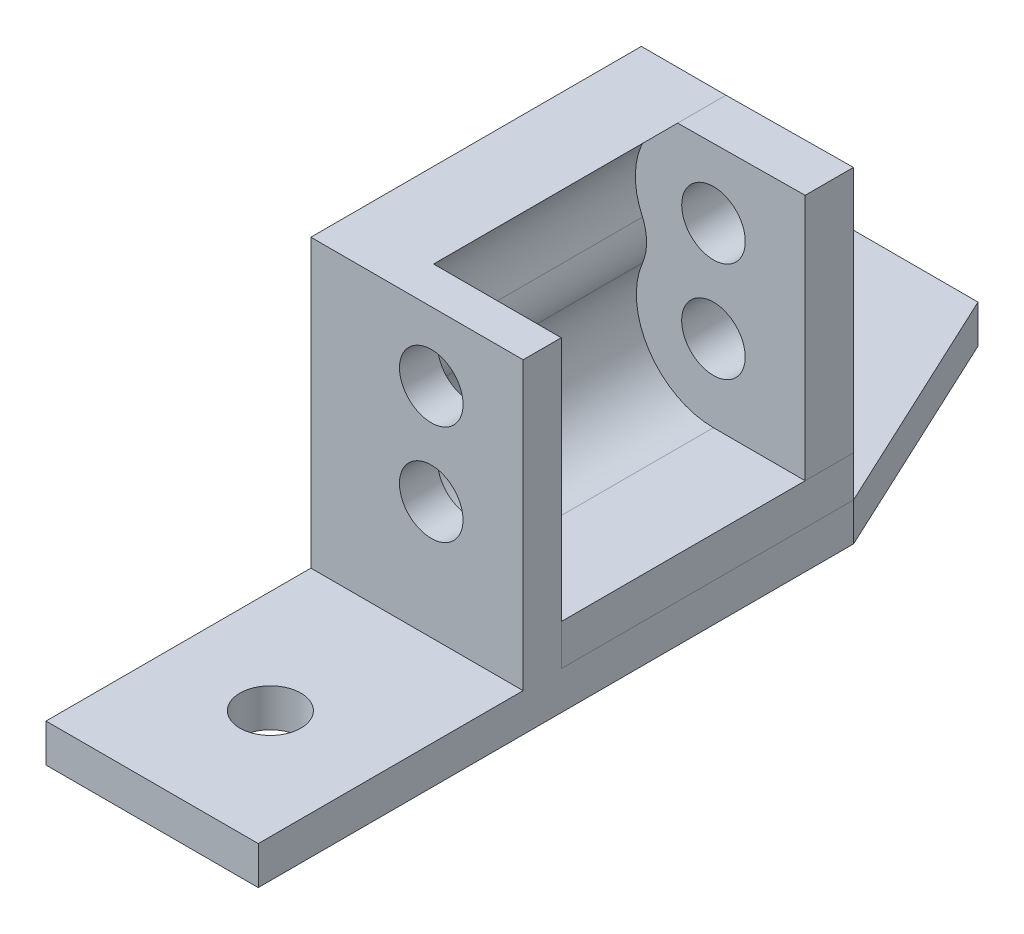
SolidWorks part; units mm, degrees
ref_plane "Front Plane" through (0, 0, 0) normal (0, 0, 1) x (1, 0, 0)
ref_plane "Top Plane" through (0, 0, 0) normal (0, 1, 0) x (1, 0, 0)
ref_plane "Right Plane" through (0, 0, 0) normal (1, 0, 0) x (0, 0, -1)
sketch "Sketch1" plane through (0, 0, 0) normal (0, 0, 1) x (1, 0, 0)
  line L0 (113.2249, 102.236) -> (113.1219, 130.8697)
  line L1 (113.1215, 130.0442) -> (113.1223, 131.6952) construction
  line L2 (113.1219, 130.8697) -> (92.018, 130.8697)
  line L3 (92.018, 130.8697) -> (92.018, 102.236)
  line L4 (92.018, 102.236) -> (113.2249, 102.236)
  line L5 (104.0412, 106.3) -> (113.2103, 106.2952)
  line L6 (128.8173, 106.287) -> (104.0412, 106.3) construction
  line L7 (104.0412, 106.3) -> (113.2103, 106.2952)
  arc A0 (104.0412, 106.3) -> (96.9606, 117.0163) centre (104.0452, 114) cw
  arc A1 (96.9606, 117.0163) -> (96.9627, 120.9912) centre (92.2865, 119.0062) ccw
  arc A2 (100.4687, 130.8697) -> (96.9627, 120.9912) centre (103.6549, 124.1774) ccw
  dimension "D1" = 5.842
  dimension "D2" = 4.064
extrude "Boss-Extrude1" add sketch "Sketch1" against normal blind 29.21 contours A2 L2 L3 L4 L0 L5 A0 A1
sketch "Sketch2" plane through (0, 0, 0) normal (0, 0, 1) x (1, 0, 0)
  line L0 (92.018, 130.8697) -> (92.018, 102.236)
  line L1 (92.018, 102.236) -> (113.2249, 102.236)
  line L2 (92.018, 130.8697) -> (113.2249, 130.8697)
  line L3 (113.2249, 130.8697) -> (113.2249, 102.236)
  circle A0 centre (104.0505, 124) radius 3.175
  circle A1 centre (104.0452, 114) radius 3.175
extrude "Boss-Extrude2" add sketch "Sketch2" along normal blind 3.81
sketch "Sketch3" plane through (0, 0, -29.21) normal (0, 0, -1) x (-1, 0, 0)
  line L0 (-113.2103, 106.2952) -> (-113.2103, 130.995)
  line L1 (-113.2103, 130.995) -> (-100.4687, 130.8697)
  line L2 (-104.0412, 106.3) -> (-113.2103, 106.2952)
  arc A0 (-100.4687, 130.8697) -> (-96.9627, 120.9912) centre (-103.6549, 124.1774) cw
  arc A1 (-96.9627, 120.9912) -> (-96.9606, 117.0163) centre (-92.2865, 119.0062) ccw
  arc A2 (-96.9606, 117.0163) -> (-104.0412, 106.3) centre (-104.0452, 114) cw
  circle A3 centre (-104.0452, 114) radius 3.175
  circle A4 centre (-104.0505, 124) radius 3.175
extrude "Boss-Extrude3" add sketch "Sketch3" against normal blind 4.826
ref_plane "Plane1" through (0, 102.236, 0) normal (0, 1, 0) x (1, 0, 0)
sketch "Sketch4" plane through (0, 102.236, 0) normal (0, 1, 0) x (1, 0, 0)
  line L0 (92.018, -3.81) -> (92.018, -30.2732)
  line L1 (113.2249, -3.81) -> (113.2249, -30.2732)
  line L2 (113.2249, -30.2732) -> (92.018, -30.2732)
  line L3 (113.2249, 29.21) -> (102.327, 52.5364)
  line L4 (102.327, 52.5364) -> (80.454, 52.5364)
  line L5 (80.454, 52.5364) -> (92.018, 29.21)
  line L6 (92.018, 29.21) -> (92.018, -3.81)
  line L7 (113.2249, 29.21) -> (113.2249, -3.81)
  circle A0 centre (96.8817, 40.9354) radius 2.9247
  circle A1 centre (102.327, -18.1626) radius 3.0423
extrude "Boss-Extrude4" add sketch "Sketch4" against normal blind 3.81
